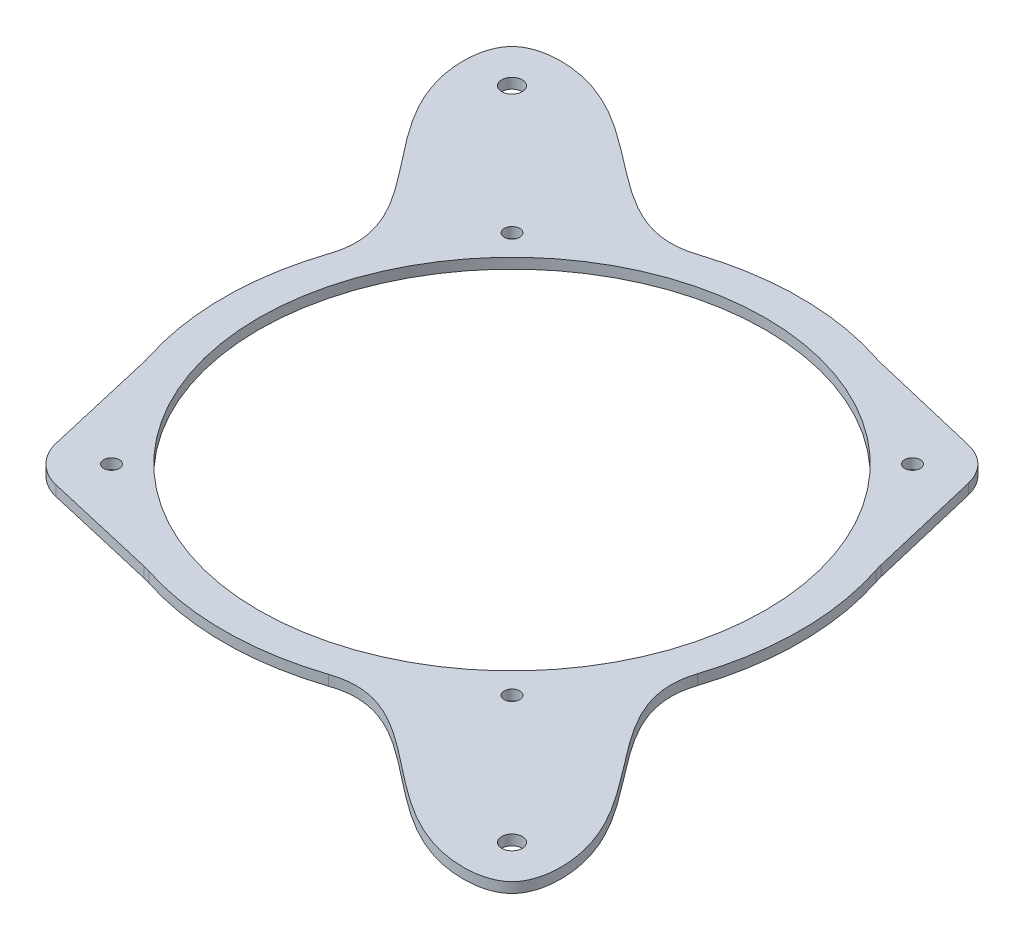
SolidWorks part; units mm, degrees
material "6061-T6 (SS)"
ref_plane "Front Plane" through (0, 0, 0) normal (0, 0, 1) x (1, 0, 0)
ref_plane "Top Plane" through (0, 0, 0) normal (0, 1, 0) x (1, 0, 0)
ref_plane "Right Plane" through (0, 0, 0) normal (1, 0, 0) x (0, 0, -1)
sketch "Sketch1" plane through (0, 0, 0) normal (0, 1, 0) x (1, 0, 0)
  line L0 (49.872, -261.8935) -> (473.872, -261.8935) construction
  line L1 (17.8971, 48.9297) -> (40.1493, 43.6512) construction
  line L2 (43.8664, 39.9141) -> (49.0252, 17.6338) construction
  line L3 (48.9297, -17.8971) -> (43.6512, -40.1493) construction
  line L4 (39.9141, -43.8664) -> (17.6338, -49.0252) construction
  line L5 (-17.8971, -48.9297) -> (-40.1493, -43.6512) construction
  line L6 (-43.8664, -39.9141) -> (-49.0252, -17.6338) construction
  line L7 (-48.9297, 17.8971) -> (-43.6512, 40.1493) construction
  line L8 (-39.9141, 43.8664) -> (-17.6338, 49.0252) construction
  line L9 (-38.8907, 38.8907) -> (38.8907, -38.8907) construction
  line L10 (-38.8907, -38.8907) -> (38.8907, 38.8907) construction
  line L12 (-38.8907, 38.8907) -> (38.8907, 38.8907) construction
  line L13 (-38.8907, 38.8907) -> (-38.8907, -38.8907) construction
  line L14 (-38.8907, -38.8907) -> (38.8907, -38.8907) construction
  line L15 (38.8907, 38.8907) -> (38.8907, -38.8907) construction
  line L16 (18.8203, 52.8217) -> (41.0725, 47.5432)
  line L21 (-47.7633, -40.8164) -> (-52.9221, -18.5361)
  line L23 (-38.8907, -38.8907) -> (-45.2538, -45.2538) construction
  line L24 (38.8907, 38.8907) -> (45.2538, 45.2538) construction
  line L25 (-70.2354, 70.2354) -> (-38.8907, 38.8907) construction
  line L26 (47.7633, 40.8164) -> (52.9221, 18.5361) construction
  line L27 (52.8217, -18.8203) -> (47.5432, -41.0725) construction
  line L28 (40.8164, -47.7633) -> (18.5361, -52.9221) construction
  line L29 (-18.8203, -52.8217) -> (-41.0725, -47.5432) construction
  line L30 (-52.8217, 18.8203) -> (-47.5432, 41.0725) construction
  line L31 (-40.8164, 47.7633) -> (-18.5361, 52.9221) construction
  line L32 (-72.3287, 60.0999) -> (-66.2143, 66.2143) construction
  line L33 (-66.2143, 66.2143) -> (-60.0999, 72.3287) construction
  line L34 (-40.8164, -47.7633) -> (-18.5361, -52.9221)
  line L35 (52.8217, 18.8203) -> (47.5432, 41.0725)
  arc A1 (-17.6338, 49.0252) -> (-15.9939, 49.4792) centre (-22.1454, 68.5097) ccw construction
  arc A2 (0.1397, 51.9998) -> (-15.9939, 49.4792) centre (0, 0) ccw construction
  arc A3 (16.2596, 49.3926) -> (0.1397, 51.9998) centre (0, 0) ccw construction
  arc A4 (16.2596, 49.3926) -> (17.8971, 48.9297) centre (22.5132, 68.3897) ccw construction
  arc A5 (43.8664, 39.9141) -> (40.1493, 43.6512) centre (38.9952, 38.7862) ccw construction
  arc A6 (49.0252, 17.6338) -> (49.4792, 15.9939) centre (68.5097, 22.1454) ccw construction
  arc A7 (49.3926, -16.2596) -> (49.4792, 15.9939) centre (0, 0) ccw construction
  arc A8 (49.3926, -16.2596) -> (48.9297, -17.8971) centre (68.3897, -22.5132) ccw construction
  arc A9 (39.9141, -43.8664) -> (43.6512, -40.1493) centre (38.7862, -38.9952) ccw construction
  arc A10 (17.6338, -49.0252) -> (15.9939, -49.4792) centre (22.1454, -68.5097) ccw construction
  arc A11 (-16.2596, -49.3926) -> (15.9939, -49.4792) centre (0, 0) ccw construction
  arc A12 (-16.2596, -49.3926) -> (-17.8971, -48.9297) centre (-22.5132, -68.3897) ccw construction
  arc A13 (-43.8664, -39.9141) -> (-40.1493, -43.6512) centre (-38.9952, -38.7862) ccw construction
  arc A14 (-49.0252, -17.6338) -> (-49.4792, -15.9939) centre (-68.5097, -22.1454) ccw construction
  arc A15 (-49.3926, 16.2596) -> (-49.4792, -15.9939) centre (0, 0) ccw construction
  arc A16 (-49.3926, 16.2596) -> (-48.9297, 17.8971) centre (-68.3897, 22.5132) ccw construction
  arc A17 (-39.9141, 43.8664) -> (-43.6512, 40.1493) centre (-38.7862, 38.9952) ccw construction
  circle A18 centre (-38.8907, 38.8907) radius 1.5
  circle A19 centre (38.8907, 38.8907) radius 1.5
  circle A20 centre (38.8907, -38.8907) radius 1.5
  circle A21 centre (-38.8907, -38.8907) radius 1.5
  arc A27 (0.1505, 55.9998) -> (-17.2242, 53.2853) centre (0, 0) ccw
  arc A28 (17.5103, 53.192) -> (0.1505, 55.9998) centre (0, 0) ccw
  arc A29 (17.5103, 53.192) -> (18.8203, 52.8217) centre (22.5132, 68.3897) ccw
  arc A30 (45.2538, 45.2538) -> (41.0725, 47.5432) centre (38.9952, 38.7862) ccw
  arc A38 (-47.7633, -40.8164) -> (-45.2538, -45.2538) centre (-38.9952, -38.7862) ccw
  arc A39 (-52.9221, -18.5361) -> (-53.2853, -17.2242) centre (-68.5097, -22.1454) ccw
  arc A40 (-53.192, 17.5103) -> (-53.2853, -17.2242) centre (0, 0) ccw
  arc A43 (47.7633, 40.8164) -> (41.0725, 47.5432) centre (38.9952, 38.7862) ccw construction
  arc A44 (52.9221, 18.5361) -> (53.2853, 17.2242) centre (68.5097, 22.1454) ccw construction
  arc A45 (53.192, -17.5103) -> (53.2853, 17.2242) centre (0, 0) ccw construction
  arc A46 (53.192, -17.5103) -> (52.8217, -18.8203) centre (68.3897, -22.5132) ccw construction
  arc A47 (40.8164, -47.7633) -> (47.5432, -41.0725) centre (38.7862, -38.9952) ccw construction
  arc A48 (18.5361, -52.9221) -> (17.2242, -53.2853) centre (22.1454, -68.5097) ccw construction
  arc A49 (-17.5103, -53.192) -> (17.2242, -53.2853) centre (0, 0) ccw construction
  arc A50 (-17.5103, -53.192) -> (-18.8203, -52.8217) centre (-22.5132, -68.3897) ccw construction
  arc A51 (-47.7633, -40.8164) -> (-41.0725, -47.5432) centre (-38.9952, -38.7862) ccw construction
  arc A52 (-53.192, 17.5103) -> (-52.8217, 18.8203) centre (-68.3897, 22.5132) ccw construction
  arc A53 (-40.8164, 47.7633) -> (-47.5432, 41.0725) centre (-38.7862, 38.9952) ccw construction
  arc A54 (-18.5361, 52.9221) -> (-17.2242, 53.2853) centre (-22.1454, 68.5097) ccw construction
  circle A55 centre (-63.6396, 63.6396) radius 2
  arc A56 (-40.8164, -47.7633) -> (-45.2538, -45.2538) centre (-38.7862, -38.9952) cw
  arc A57 (-18.5361, -52.9221) -> (-17.2242, -53.2853) centre (-22.1454, -68.5097) cw
  arc A58 (17.5103, -53.192) -> (-17.2242, -53.2853) centre (0, 0) cw
  arc A59 (55.9998, 0.1505) -> (53.2853, -17.2242) centre (0, 0) cw
  arc A60 (53.192, 17.5103) -> (55.9998, 0.1505) centre (0, 0) cw
  arc A61 (53.192, 17.5103) -> (52.8217, 18.8203) centre (68.3897, 22.5132) cw
  arc A62 (45.2538, 45.2538) -> (47.5432, 41.0725) centre (38.7862, 38.9952) cw
  circle A63 centre (63.6396, -63.6396) radius 2
  circle A64 centre (0, 0) radius 49.2
  spline S0 degree 3 poles (-53.192, 17.5103) (-48.007, 32.4895) (-74.6637, 45.2713) (-72.0883, 72.0956) (-45.2822, 74.6216) (-32.1391, 48.3634) (-17.2242, 53.2853) knots 0 0 0 0 0.409379 0.499716 0.590053 1 1 1 1
  spline S1 degree 3 poles (17.5103, -53.192) (32.4895, -48.007) (45.2713, -74.6637) (72.0956, -72.0883) (74.6216, -45.2822) (48.3634, -32.1391) (53.2853, -17.2242) knots 0 0 0 0 0.409379 0.499716 0.590053 1 1 1 1
  dimension "D1" = 3
  dimension "D2" = 4
  dimension "D3" = 4
  dimension "D4" = 180
  dimension "D5" = 98.4
extrude "Boss-Extrude1" add sketch "Sketch1" along normal blind 2
